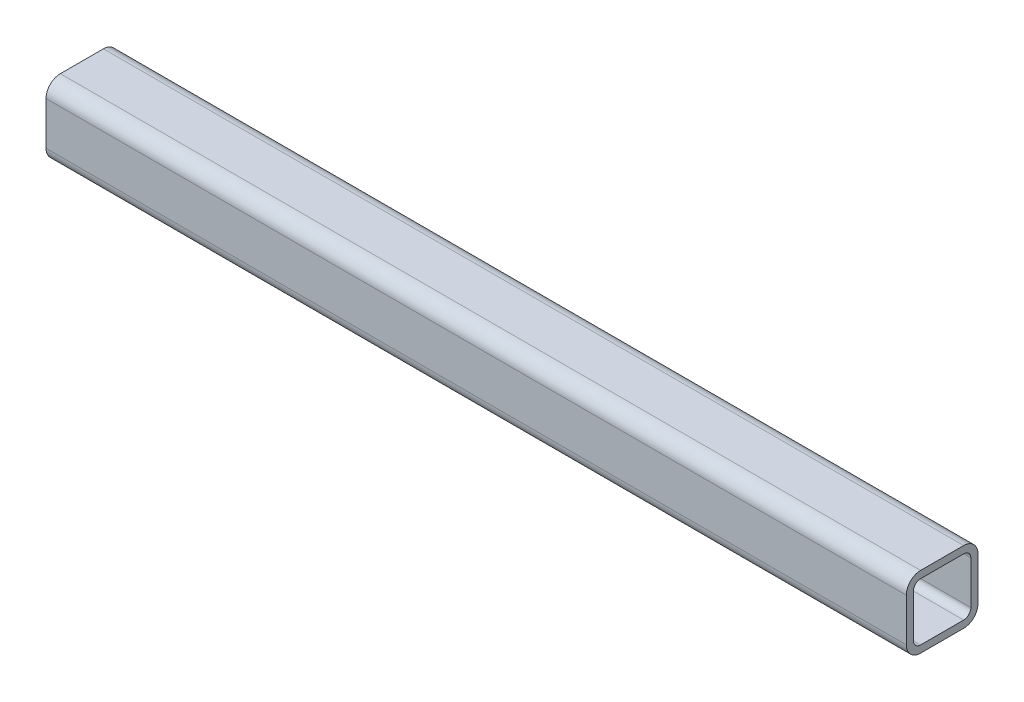
SolidWorks part; units mm, degrees
material "ASTM A36 Acero"
ref_plane "Alzado" through (0, 0, 0) normal (0, 0, 1) x (1, 0, 0)
ref_plane "Planta" through (0, 0, 0) normal (0, 1, 0) x (1, 0, 0)
ref_plane "Vista lateral" through (0, 0, 0) normal (1, 0, 0) x (0, 0, -1)
sketch "Croquis1" plane through (0, 0, 0) normal (0, 0, 1) x (1, 0, 0)
  line L0 (0, 0) -> (600, 0)
  dimension "D1" = 600
other "Tube (square) RHS50X50X5(1)"
ref_plane "Plano1" through (0, 0, 0) normal (1, 0, 0) x (0, 1, 0)
sketch "Sketch1" plane through (0, 0, 0) normal (1, 0, 0) x (0, 1, 0)
  line L0 (-15, -20) -> (15, -20)
  line L1 (-20, -15) -> (-20, 15)
  line L2 (15, 20) -> (-15, 20)
  line L3 (20, 15) -> (20, -15)
  line L4 (-15, -25) -> (15, -25)
  line L5 (-25, -15) -> (-25, 15)
  line L6 (15, 25) -> (-15, 25)
  line L7 (25, 15) -> (25, -15)
  line L8 (-25, 0) -> (-20, 0) construction
  line L9 (-20, 0) -> (20, 0) construction
  line L10 (20, 0) -> (25, 0) construction
  line L11 (0, 25) -> (0, 20) construction
  line L12 (0, 20) -> (0, -20) construction
  line L13 (0, -20) -> (0, -25) construction
  arc A0 (25, 15) -> (15, 25) centre (15, 15) ccw
  arc A1 (15, -25) -> (25, -15) centre (15, -15) ccw
  arc A2 (-25, -15) -> (-15, -25) centre (-15, -15) ccw
  arc A3 (-15, 25) -> (-25, 15) centre (-15, 15) ccw
  arc A4 (-15, 20) -> (-20, 15) centre (-15, 15) ccw
  arc A5 (20, 15) -> (15, 20) centre (15, 15) ccw
  arc A6 (15, -20) -> (20, -15) centre (15, -15) ccw
  arc A7 (-20, -15) -> (-15, -20) centre (-15, -15) ccw
  point P6 (-25, 25)
  point P33 (0, 0)
  point P35 (25, 25)
  point P36 (-25, -25)
  point P37 (25, -25)
  dimension "D1" = 10
  dimension "Thickness" = 5
  dimension "V_leg" = 50
  dimension "H_leg" = 50
